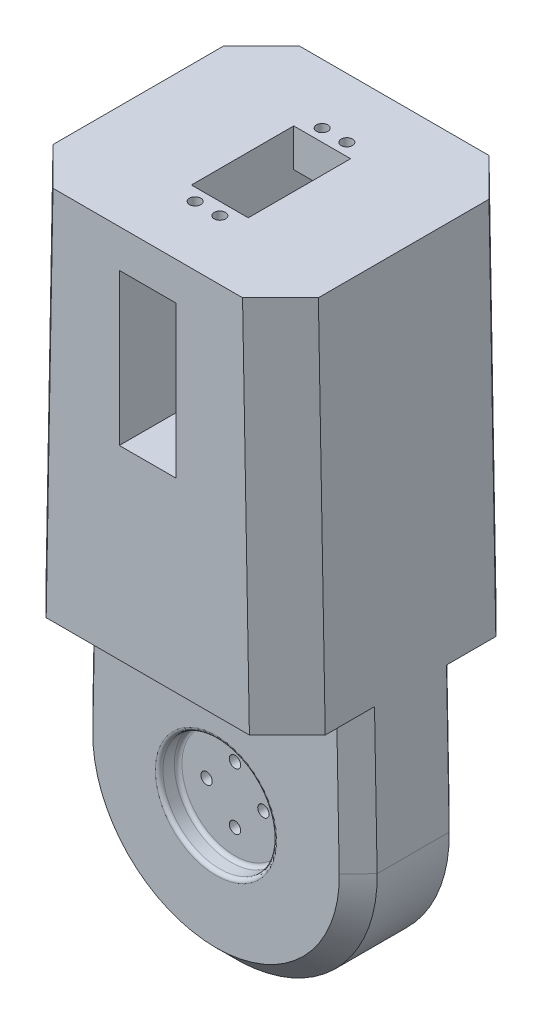
SolidWorks part; units mm, degrees
ref_plane "Front Plane" through (0, 0, 0) normal (0, 0, 1) x (1, 0, 0)
ref_plane "Top Plane" through (0, 0, 0) normal (0, 1, 0) x (1, 0, 0)
ref_plane "Right Plane" through (0, 0, 0) normal (1, 0, 0) x (0, 0, -1)
sketch "Sketch1" plane through (0, 0, 0) normal (0, 0, 1) x (1, 0, 0)
  line L0 (-35, 137.5) -> (35, 137.5)
  line L1 (0, -1000) -> (0, 49000) construction
  line L2 (35, 137.5) -> (37.4938, 0.6834)
  line L3 (-35, 137.5) -> (-37.4938, 0.6834)
  arc A0 (-37.4938, 0.6834) -> (37.4938, 0.6834) centre (0, 0) ccw
  point P4 (0, 0)
  point P10 (0, 137.5)
  dimension "D1" = 75
  dimension "D2" = 70
  dimension "D3" = 137.5
extrude "Boss-Extrude1" add sketch "Sketch1" along normal blind 65
sketch "Sketch2" plane through (0, 0, 0) normal (1, 0, 0) x (0, 0, -1)
  line L0 (0, 0.6834) -> (0, 137.5) construction
  line L1 (-65, -37.5) -> (0, -37.5)
  line L2 (-65, -37.5) -> (-65, 38.5)
  line L3 (-65, 38.5) -> (0, 38.5)
  line L4 (0, -37.5) -> (0, 38.5)
  line L6 (-47, 38.5) -> (-18, 38.5)
  line L7 (-47, 38.5) -> (-47, -37.5)
  line L8 (-47, -37.5) -> (-18, -37.5)
  line L9 (-18, 38.5) -> (-18, -37.5)
  dimension "D1" = 76
  dimension "D2" = 29
  dimension "D3" = 18
extrude "Cut-Extrude1" cut sketch "Sketch2" against normal mid plane 97 contours L7 L3 L2 L1 | L3 L9 L1 L4
chamfer "Chamfer1" distance 10 4 edges at (-35.9022, 88, 0) (35.9022, 88, 0) (35.9022, 88, 65) (-35.9022, 88, 65)
chamfer "Chamfer2" distance 5 angle 45 6 edges at (-37.1491, 19.5917, 18) (0, -37.5, 18) (37.1491, 19.5917, 18) (-37.1491, 19.5917, 47) (0, -37.5, 47) (37.1491, 19.5917, 47)
sketch "Sketch3" plane through (0, 0, 47) normal (0, 0, 1) x (1, 0, 0)
  circle A0 centre (0, 0) radius 15
  dimension "D1" = 30
extrude "Cut-Extrude2" cut sketch "Sketch3" against normal mid plane 10
sketch "Sketch5" plane through (0, 0, 42) normal (0, 0, 1) x (1, 0, 0)
  line L0 (-15, 0) -> (15, 0) construction
  line L1 (0, 20.7072) -> (0, -20.7072) construction
  circle A2 centre (0, 0) radius 15 construction
  circle A3 centre (0, 0) radius 15 construction
  circle A4 centre (0, 7.5) radius 1.5
  circle A5 centre (7.5, 0) radius 1.5
  circle A6 centre (0, -7.5) radius 1.5
  circle A7 centre (-7.5, 0) radius 1.5
  point P9 (0, 0)
  point P14 (0, 0)
  point P25 (0, 0)
  dimension "D1" = 3
  dimension "D2" = 7.5
  dimension "D3" = 4
extrude "Cut-Extrude3" cut sketch "Sketch5" against normal mid plane 7.5
fillet "Fillet1" radius 1 2 edges at (15, 0, 42) (0, -15, 47)
sketch "Sketch6" plane through (0, 0, 65) normal (0, 0, 1) x (1, 0, 0)
  line L0 (0, 137.5) -> (0, 38.5) construction
  line L3 (24.9983, 137.5) -> (-24.9983, 137.5) construction
  line L8 (-31.8037, 38.5) -> (31.8037, 38.5) construction
  line L10 (-7.5, 127.5) -> (7.5, 127.5)
  line L11 (-7.5, 127.5) -> (-7.5, 87.5)
  line L12 (-7.5, 87.5) -> (7.5, 87.5)
  line L13 (7.5, 127.5) -> (7.5, 87.5)
  line L14 (-7.5, 127.5) -> (7.5, 87.5) construction
  line L15 (-7.5, 87.5) -> (7.5, 127.5) construction
  point P7 (0, 107.5)
  dimension "D1" = 40
  dimension "D2" = 15
  dimension "D3" = 10
extrude "Cut-Extrude4" cut sketch "Sketch6" against normal through all
sketch "Sketch7" plane through (0, 137.5, 0) normal (0, 1, 0) x (1, 0, 0)
  line L0 (0, 0) -> (0, -65) construction
  line L1 (24.9983, -65) -> (-24.9983, -65) construction
  line L2 (-7.5, -32.5) -> (7.5, -32.5) construction
  line L3 (-7.5, -19) -> (7.5, -19)
  line L4 (-7.5, -19) -> (-7.5, -46)
  line L5 (-7.5, -46) -> (7.5, -46)
  line L6 (7.5, -19) -> (7.5, -46)
  line L7 (-7.5, -19) -> (7.5, -46) construction
  line L8 (-7.5, -46) -> (7.5, -19) construction
  circle A0 centre (-3.25, -15.75) radius 1.5
  circle A1 centre (3.25, -15.75) radius 1.5
  circle A2 centre (3.25, -49.25) radius 1.5
  circle A3 centre (-3.25, -49.25) radius 1.5
  point P5 (0, -32.5)
  dimension "D3" = 3
  dimension "D1" = 15
  dimension "D2" = 27
  dimension "D4" = 3.25
  dimension "D5" = 3.25
extrude "Cut-Extrude5" cut sketch "Sketch7" against normal up to surface (10 mm away) up to face at (0, 127.5, 32.5)
sketch "Sketch8" plane through (0, 137.5, 0) normal (0, 1, 0) x (1, 0, 0)
  line L0 (0, -19) -> (0, -46) construction
  line L1 (7.5, -19) -> (-7.5, -19) construction
  line L2 (-7.5, -46) -> (7.5, -46) construction
  circle A0 centre (0, -32.5) radius 3.75 construction
  dimension "D1" = 7.5
